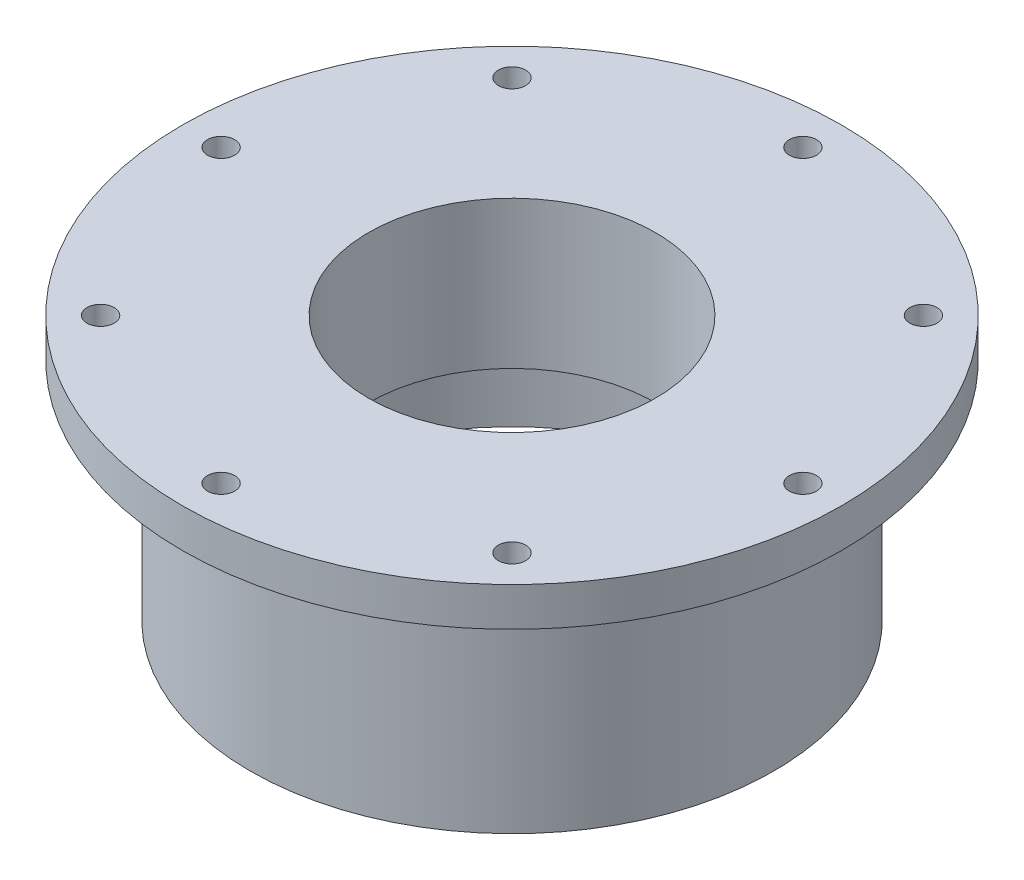
SolidWorks part; units mm, degrees
ref_plane "Front Plane" through (0, 0, 0) normal (0, 0, 1) x (1, 0, 0)
ref_plane "Top Plane" through (0, 0, 0) normal (0, 1, 0) x (1, 0, 0)
ref_plane "Right Plane" through (0, 0, 0) normal (1, 0, 0) x (0, 0, -1)
sketch "Sketch1" plane through (0, 0, 0) normal (0, 1, 0) x (1, 0, 0)
  line L0 (0, 56.8581) -> (0, -58.2457) construction
  line L1 (-55.3664, 0) -> (59.1638, 0) construction
  circle A0 centre (0, 0) radius 42.5
  circle A1 centre (0, 0) radius 18.5
  circle A2 centre (0, 37.5) radius 1.75
  circle A3 centre (0, 0) radius 37.5 construction
  circle A4 centre (26.5165, 26.5165) radius 1.75
  circle A5 centre (37.5, 0) radius 1.75
  circle A6 centre (26.5165, -26.5165) radius 1.75
  circle A7 centre (0, -37.5) radius 1.75
  circle A8 centre (-26.5165, -26.5165) radius 1.75
  circle A9 centre (-37.5, 0) radius 1.75
  circle A10 centre (-26.5165, 26.5165) radius 1.75
  point P27 (0, 0)
  dimension "D1" = 85
  dimension "D2" = 37
  dimension "D3" = 75
  dimension "D4" = 3.5
  dimension "D5" = 8
extrude "Boss-Extrude1" add sketch "Sketch1" along normal mid plane 5
sketch "Sketch2" plane through (0, -2.5, 0) normal (0, 1, 0) x (1, 0, 0)
  circle A0 centre (0, 0) radius 18.5
  circle A1 centre (0, 0) radius 33.75
  circle A2 centre (0, 0) radius 18.5 construction
  dimension "D1" = 67.5
extrude "Boss-Extrude2" add sketch "Sketch2" against normal blind 14
sketch "Sketch3" plane through (0, -16.5, 0) normal (0, -1, 0) x (1, 0, 0)
  circle A0 centre (0, 0) radius 33.75
  circle A1 centre (0, 0) radius 33.75 construction
  circle A2 centre (0, 0) radius 30.5
  dimension "D1" = 61
extrude "Boss-Extrude3" add sketch "Sketch3" along normal blind 15
